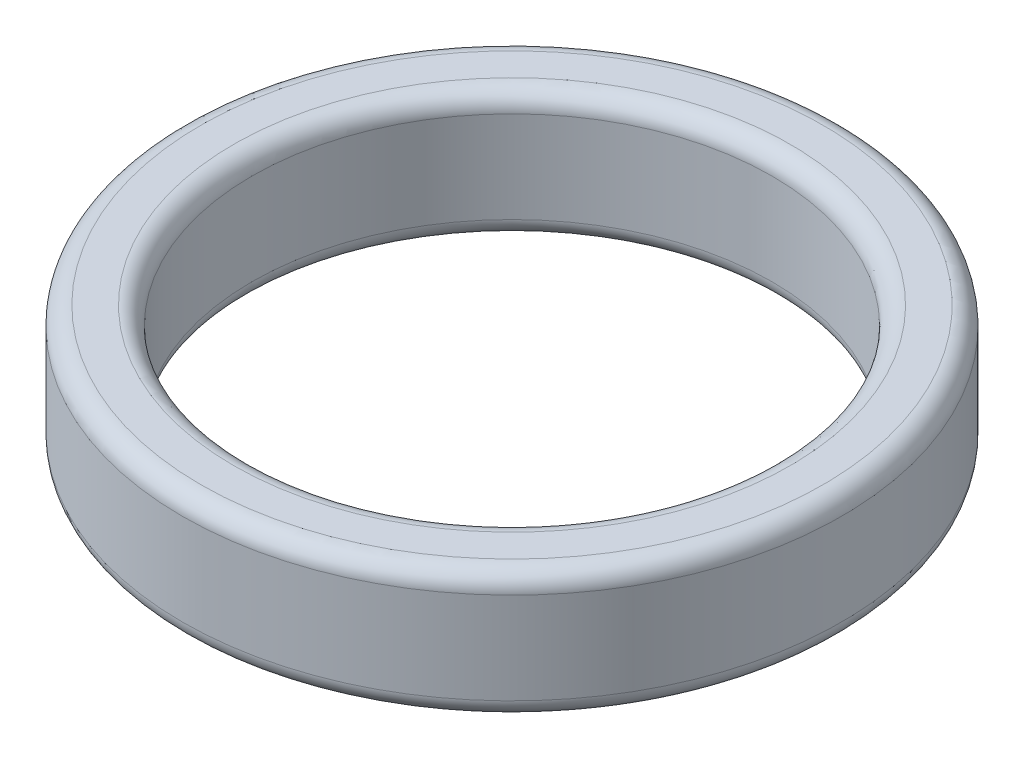
SolidWorks part; units mm, degrees
material "Резина"
ref_plane "Спереди" through (0, 0, 0) normal (0, 0, 1) x (1, 0, 0)
ref_plane "Сверху" through (0, 0, 0) normal (0, 1, 0) x (1, 0, 0)
ref_plane "Справа" through (0, 0, 0) normal (1, 0, 0) x (0, 0, -1)
other "Табл. исп."
sketch "Эскиз1" plane through (0, 0, 0) normal (0, 1, 0) x (1, 0, 0)
  circle A0 centre (0, 0) radius 9
  circle A1 centre (0, 0) radius 7.1
  dimension "D1" = 18
  dimension "D2" = 14.2
extrude "Бобышка-Вытянуть1" add sketch "Эскиз1" along normal blind 3.5
fillet "Скругление1" radius 0.5 4 edges at (0, 0, 7.1) (0, 3.5, 7.1) (0, 0, 9) (0, 3.5, 9)
